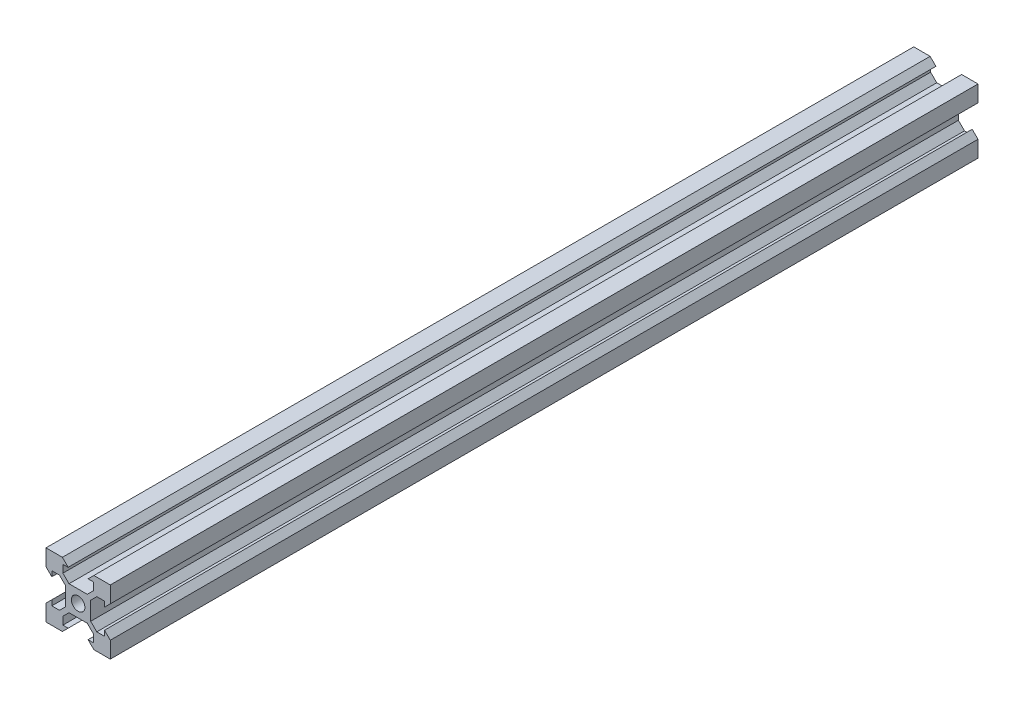
SolidWorks part; units mm, degrees
material "6063-T5"
ref_plane "Front Plane" through (0, 0, 0) normal (0, 0, 1) x (1, 0, 0)
ref_plane "Top Plane" through (0, 0, 0) normal (0, 1, 0) x (1, 0, 0)
ref_plane "Right Plane" through (0, 0, 0) normal (1, 0, 0) x (0, 0, -1)
sketch "Sketch1" plane through (0, 0, 0) normal (0, 0, 1) x (1, 0, 0)
  line L0 (-3.9007, -2.84) -> (-3.9007, 2.84)
  line L1 (-3.9007, 2.84) -> (-5.8007, 4.74)
  line L2 (-5.8007, 4.74) -> (-8.2, 4.74)
  line L3 (-8.2, 4.74) -> (-8.2, 3.1)
  line L4 (-10, 10) -> (-1.4849, 1.4849) construction
  line L5 (0, 3.9007) -> (-2.84, 3.9007)
  line L6 (-2.84, 3.9007) -> (-4.74, 5.8007)
  line L7 (-4.74, 8.2) -> (-3.1, 8.2)
  line L8 (-4.74, 5.8007) -> (-4.74, 8.2)
  line L9 (-3.1, 8.2) -> (-4.9, 10)
  line L10 (-4.9, 10) -> (-10, 10)
  line L11 (-10, 10) -> (-10, 4.9)
  line L12 (-8.2, 3.1) -> (-10, 4.9)
  line L13 (0, 3.9007) -> (0, -3.9007) construction
  line L14 (10, 10) -> (1.4849, 1.4849) construction
  line L15 (8.2, 3.1) -> (10, 4.9)
  line L16 (10, 10) -> (10, 4.9)
  line L17 (4.9, 10) -> (10, 10)
  line L18 (3.1, 8.2) -> (4.9, 10)
  line L19 (4.74, 5.8007) -> (4.74, 8.2)
  line L20 (4.74, 8.2) -> (3.1, 8.2)
  line L21 (2.84, 3.9007) -> (4.74, 5.8007)
  line L22 (8.2, 4.74) -> (8.2, 3.1)
  line L23 (5.8007, 4.74) -> (8.2, 4.74)
  line L24 (3.9007, 2.84) -> (5.8007, 4.74)
  line L25 (2.84, 3.9007) -> (0, 3.9007)
  line L26 (3.9007, 2.84) -> (3.9007, -2.84)
  line L27 (-3.9007, 0) -> (3.9007, 0) construction
  line L28 (10, -10) -> (1.4849, -1.4849) construction
  line L29 (-10, -10) -> (-1.4849, -1.4849) construction
  line L30 (2.84, -3.9007) -> (0, -3.9007)
  line L31 (3.9007, -2.84) -> (5.8007, -4.74)
  line L32 (5.8007, -4.74) -> (8.2, -4.74)
  line L33 (8.2, -4.74) -> (8.2, -3.1)
  line L34 (2.84, -3.9007) -> (4.74, -5.8007)
  line L35 (4.74, -8.2) -> (3.1, -8.2)
  line L36 (4.74, -5.8007) -> (4.74, -8.2)
  line L37 (3.1, -8.2) -> (4.9, -10)
  line L38 (4.9, -10) -> (10, -10)
  line L39 (10, -10) -> (10, -4.9)
  line L40 (8.2, -3.1) -> (10, -4.9)
  line L41 (-8.2, -3.1) -> (-10, -4.9)
  line L42 (-10, -10) -> (-10, -4.9)
  line L43 (-4.9, -10) -> (-10, -10)
  line L44 (-3.1, -8.2) -> (-4.9, -10)
  line L45 (-4.74, -5.8007) -> (-4.74, -8.2)
  line L46 (-4.74, -8.2) -> (-3.1, -8.2)
  line L47 (-2.84, -3.9007) -> (-4.74, -5.8007)
  line L48 (0, -3.9007) -> (-2.84, -3.9007)
  line L49 (-8.2, -4.74) -> (-8.2, -3.1)
  line L50 (-5.8007, -4.74) -> (-8.2, -4.74)
  line L51 (-3.9007, -2.84) -> (-5.8007, -4.74)
  circle A0 centre (0, 0) radius 2.1
  point P10 (-4.8507, 3.79)
  dimension "D1" = 4.2
  dimension "D2" = 5.68
  dimension "D3" = 1.64
  dimension "D4" = 6.2
  dimension "D5" = 0.75
  dimension "D6" = 10
  dimension "D7" = 90
  dimension "D8" = 1.8
extrude "Boss-Extrude1" add sketch "Sketch1" along normal mid plane 270
